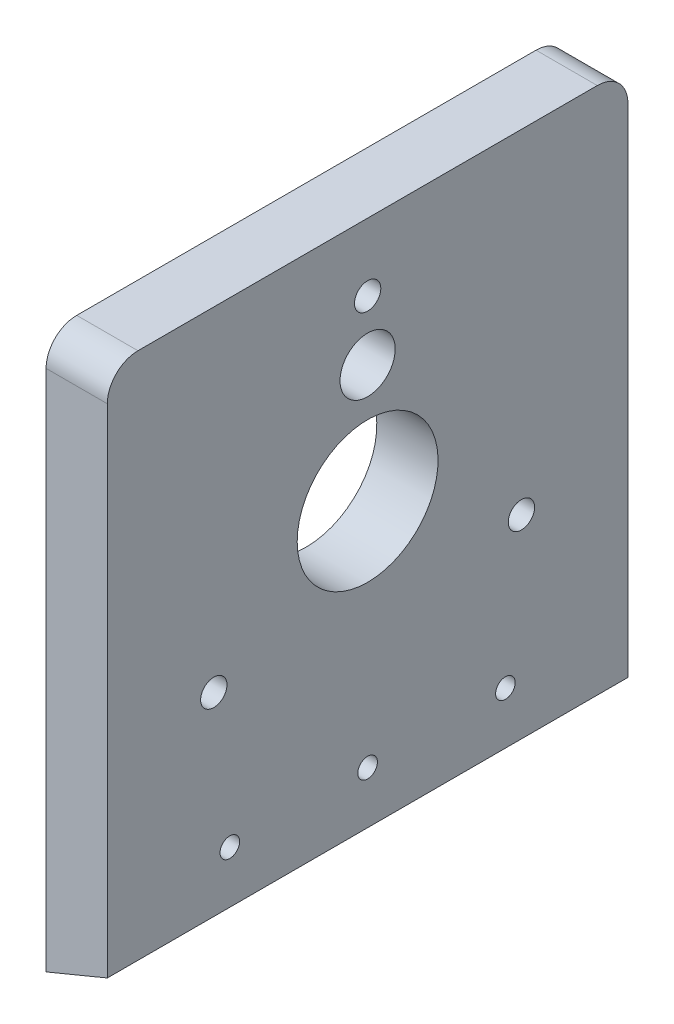
SolidWorks part; units mm, degrees
ref_plane "Front Plane" through (0, 0, 0) normal (0, 0, 1) x (1, 0, 0)
ref_plane "Top Plane" through (0, 0, 0) normal (0, 1, 0) x (1, 0, 0)
ref_plane "Right Plane" through (0, 0, 0) normal (1, 0, 0) x (0, 0, -1)
sketch "Sketch2" plane through (0, 0, 0) normal (0, 0, 1) x (1, 0, 0)
  line L0 (0, 0) -> (0, 86.2)
  line L1 (0, 86.2) -> (-10, 86.2)
  line L2 (-10, 86.2) -> (-10, -4.1421)
  line L3 (-10, -4.1421) -> (0, 0)
  dimension "D1" = 86.2
  dimension "D2" = 247.5
  dimension "D3" = 10
extrude "Boss-Extrude1" add sketch "Sketch2" along normal blind 85
sketch "Sketch3" plane through (-10, 0, 0) normal (-1, 0, 0) x (0, 0, 1)
  line L0 (42.5, 86.2) -> (42.5, -4.1421) construction
  line L1 (85, 86.2) -> (0, 86.2) construction
  line L2 (85, -4.1421) -> (0, -4.1421) construction
  circle A0 centre (42.5, 46.2) radius 11.5
  circle A1 centre (42.5, 65.45) radius 4.5
  circle A2 centre (42.5, 75.2) radius 2.15
  circle A3 centre (67.6147, 31.7) radius 2.15
  circle A4 centre (17.3853, 31.7) radius 2.15
  point P19 (42.5, 46.2)
  dimension "D1" = 23
  dimension "D3" = 9
  dimension "D5" = 4.3
  dimension "D2" = 40
  dimension "D4" = 19.25
  dimension "D6" = 29
  dimension "D7" = 3
extrude "Cut-Extrude1" cut sketch "Sketch3" against normal blind 85
sketch "Sketch4" plane through (0, 0, 0) normal (1, 0, 0) x (0, 0, -1)
  line L0 (-85, 0) -> (0, 0) construction
  line L1 (-85, 0) -> (-85, 86.2) construction
  line L2 (0, 0) -> (0, 86.2) construction
  circle A0 centre (-65, 8.5) radius 1.6
  circle A1 centre (-20, 8.5) radius 1.6
  circle A2 centre (-42.5, 8.5) radius 1.6
  dimension "D1" = 3.2
  dimension "D2" = 3.2
  dimension "D7" = 3.2
  dimension "D3" = 8.5
  dimension "D4" = 8.5
  dimension "D5" = 20
  dimension "D6" = 20
  dimension "D8" = 8.5
  dimension "D9" = 42.5
extrude "Cut-Extrude2" cut sketch "Sketch4" against normal blind 85
fillet "Fillet1" radius 5 2 edges at (-5, 86.2, 0) (-5, 86.2, 85)
